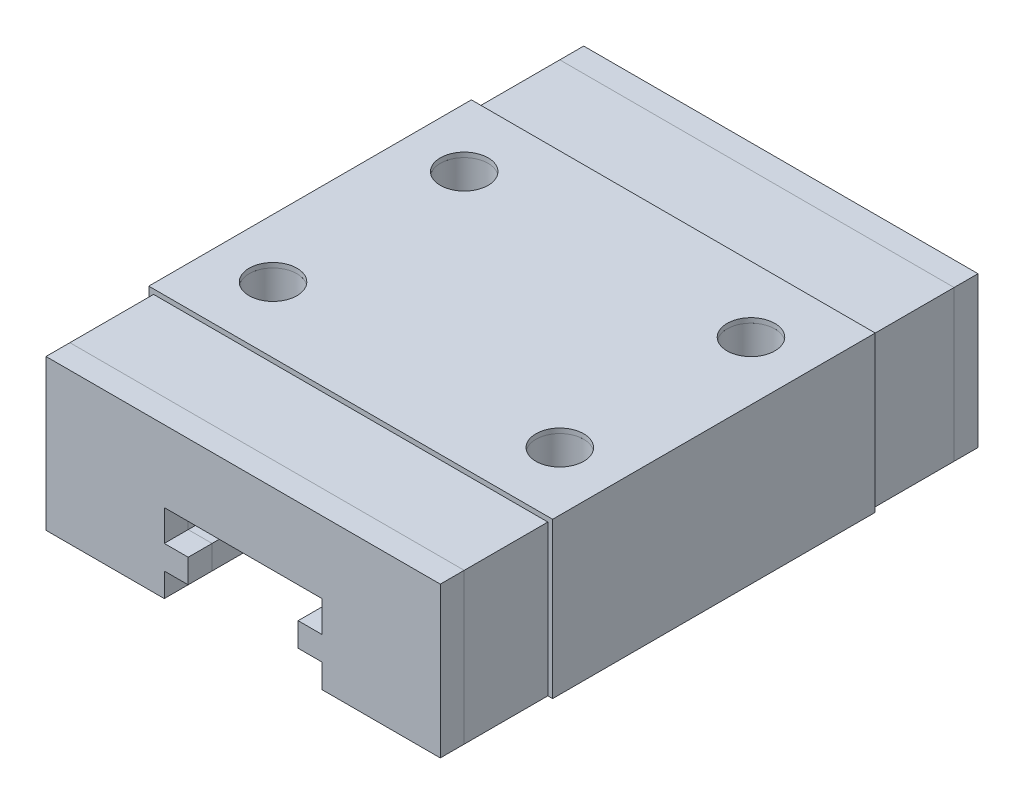
SolidWorks part; units mm, degrees
material "1060 合金"
ref_plane "前视基准面" through (0, 0, 0) normal (0, 0, 1) x (1, 0, 0)
ref_plane "上视基准面" through (0, 0, 0) normal (0, 1, 0) x (1, 0, 0)
ref_plane "右视基准面" through (0, 0, 0) normal (1, 0, 0) x (0, 0, -1)
sketch "草图1" plane through (0, 0, 0) normal (0, 0, 1) x (1, 0, 0)
  line L0 (0, 0) -> (0, 6.3)
  line L1 (0, 6.3) -> (16.5, 6.3)
  line L2 (16.5, 6.3) -> (16.5, 0)
  line L3 (16.5, 0) -> (11.55, 0)
  line L4 (0, 0) -> (4.95, 0)
  line L5 (4.95, 0) -> (4.95, 1)
  line L6 (4.95, 1) -> (5.95, 1)
  line L7 (5.95, 1) -> (5.95, 2)
  line L8 (5.95, 2) -> (4.95, 2)
  line L9 (4.95, 2) -> (4.95, 3.3)
  line L10 (4.95, 3.3) -> (11.55, 3.3)
  line L11 (11.55, 3.3) -> (11.55, 2)
  line L12 (11.55, 2) -> (10.55, 2)
  line L13 (10.55, 2) -> (10.55, 1)
  line L14 (10.55, 1) -> (11.55, 1)
  line L15 (11.55, 1) -> (11.55, 0)
  line L16 (8.25, 6.3) -> (8.25, 0) construction
  dimension "D1" = 16.5
  dimension "D2" = 6.3
  dimension "D3" = 6.6
  dimension "D4" = 3
  dimension "D5" = 1.3
  dimension "D6" = 1
  dimension "D7" = 1
extrude "凸台-拉伸1" add sketch "草图1" along normal blind 1
sketch "草图2" plane through (0, 0, 1) normal (0, 0, 1) x (1, 0, 0)
  line L0 (4.95, 0) -> (4.95, 1)
  line L1 (4.95, 1) -> (5.95, 1)
  line L2 (5.95, 1) -> (5.95, 2)
  line L3 (5.95, 2) -> (4.95, 2)
  line L4 (4.95, 2) -> (4.95, 3.3)
  line L5 (4.95, 3.3) -> (11.55, 3.3)
  line L6 (11.55, 3.3) -> (11.55, 2)
  line L7 (11.55, 2) -> (10.55, 2)
  line L8 (10.55, 2) -> (10.55, 1)
  line L9 (10.55, 1) -> (11.55, 1)
  line L10 (11.55, 1) -> (11.55, 0)
  line L11 (11.55, 0) -> (16.5, 0)
  line L13 (16.5, 0) -> (16.5, 6.3)
  line L14 (16.5, 6.3) -> (0, 6.3)
  line L15 (0, 6.3) -> (0, 0)
  line L16 (0, 0) -> (4.95, 0) construction
  line L17 (0, 0) -> (4.95, 0)
extrude "凸台-拉伸2" add sketch "草图2" along normal blind 20.5 separate body
sketch "草图3" plane through (0, 0, 21.5) normal (0, 0, 1) x (1, 0, 0)
  line L17 (0, 0) -> (4.95, 0)
  line L18 (4.95, 0) -> (4.95, 1)
  line L19 (4.95, 1) -> (5.95, 1)
  line L20 (5.95, 1) -> (5.95, 2)
  line L21 (5.95, 2) -> (4.95, 2)
  line L22 (4.95, 2) -> (4.95, 3.3)
  line L23 (4.95, 3.3) -> (11.55, 3.3)
  line L24 (11.55, 3.3) -> (11.55, 2)
  line L25 (11.55, 2) -> (10.55, 2)
  line L26 (10.55, 2) -> (10.55, 1)
  line L27 (10.55, 1) -> (11.55, 1)
  line L28 (11.55, 1) -> (11.55, 0)
  line L29 (11.55, 0) -> (16.5, 0)
  line L30 (16.5, 0) -> (16.5, 6.3)
  line L31 (16.5, 6.3) -> (0, 6.3)
  line L32 (0, 6.3) -> (0, 0)
  line L33 (0, 0) -> (4.95, 0)
  line L34 (4.95, 0) -> (4.95, 1)
  line L35 (4.95, 1) -> (5.95, 1)
  line L36 (5.95, 1) -> (5.95, 2)
  line L37 (5.95, 2) -> (4.95, 2)
  line L38 (4.95, 2) -> (4.95, 3.3)
  line L39 (4.95, 3.3) -> (11.55, 3.3)
  line L40 (11.55, 3.3) -> (11.55, 2)
  line L41 (11.55, 2) -> (10.55, 2)
  line L42 (10.55, 2) -> (10.55, 1)
  line L43 (10.55, 1) -> (11.55, 1)
  line L44 (11.55, 1) -> (11.55, 0)
  line L45 (11.55, 0) -> (16.5, 0)
  line L46 (16.5, 0) -> (16.5, 6.3)
  line L47 (16.5, 6.3) -> (0, 6.3)
  line L48 (0, 6.3) -> (0, 0)
  dimension "D1" = 0
extrude "凸台-拉伸3" add sketch "草图3" along normal blind 1
ref_plane "基准面1" through (0, 0, 4.5) normal (0, 0, 1) x (1, 0, 0)
fillet "圆角1" radius 0.25 12 edges at (4.95, 0, 0.5) (11.55, 0, 0.5) (11.55, 3.3, 0.5) (4.95, 3.3, 0.5) (4.95, 2, 0.5) (5.95, 2, 0.5) (5.95, 1, 0.5) (4.95, 1, 0.5) (11.55, 1, 0.5) (11.55, 2, 0.5) (10.55, 1, 0.5) (10.55, 2, 0.5)
sketch "草图4" plane through (0, 0, 4.5) normal (0, 0, 1) x (1, 0, 0)
  line L0 (8.25, 6.3) -> (8.25, 3.3) construction
  line L1 (0, 0) -> (-0.2, 0)
  line L2 (-0.2, 0) -> (-0.2, 6.5)
  line L3 (-0.2, 6.5) -> (8.25, 6.5)
  line L4 (8.25, 6.5) -> (8.25, 6.3)
  line L5 (8.25, 6.3) -> (0, 6.3)
  line L6 (0, 6.3) -> (0, 0)
  line L7 (16.5, 6.3) -> (0, 6.3) construction
  line L8 (4.95, 3.3) -> (11.55, 3.3) construction
  line L9 (0, 6.3) -> (0, 0) construction
  line L10 (16.5, 6.3) -> (16.5, 0)
  line L11 (8.25, 6.3) -> (16.5, 6.3)
  line L12 (8.25, 6.5) -> (8.25, 6.3)
  line L13 (16.7, 6.5) -> (8.25, 6.5)
  line L14 (16.7, 0) -> (16.7, 6.5)
  line L15 (16.5, 0) -> (16.7, 0)
  dimension "D1" = 0.2
  dimension "D2" = 0.2
extrude "凸台-拉伸4" add sketch "草图4" along normal blind 13.5 contours L10 L15 L14 L13 L4 L11
sketch "草图5" plane through (0, 6.5, 0) normal (0, 1, 0) x (1, 0, 0)
  line L0 (-0.2, -11.25) -> (16.7, -11.25) construction
  line L1 (-0.2, -18) -> (-0.2, -4.5) construction
  line L3 (8.25, -4.5) -> (8.25, -18) construction
  line L6 (16.7, -18) -> (16.7, -4.5) construction
  line L7 (16.7, -4.5) -> (-0.2, -4.5) construction
  line L8 (16.7, -18) -> (-0.2, -18) construction
  circle A0 centre (2.25, -7.25) radius 1
  circle A1 centre (2.25, -15.25) radius 1
  circle A2 centre (14.25, -15.25) radius 1
  circle A3 centre (14.25, -7.25) radius 1
  dimension "D2" = 12
  dimension "D1" = 2
  dimension "D3" = 8
extrude "切除-拉伸1" cut sketch "草图5" against normal blind 4 contours A1 | A2 | A3 | A0
ref_plane "基准面2" through (8.25, 0, 0) normal (-1, 0, 0) x (0, 0, 1)
